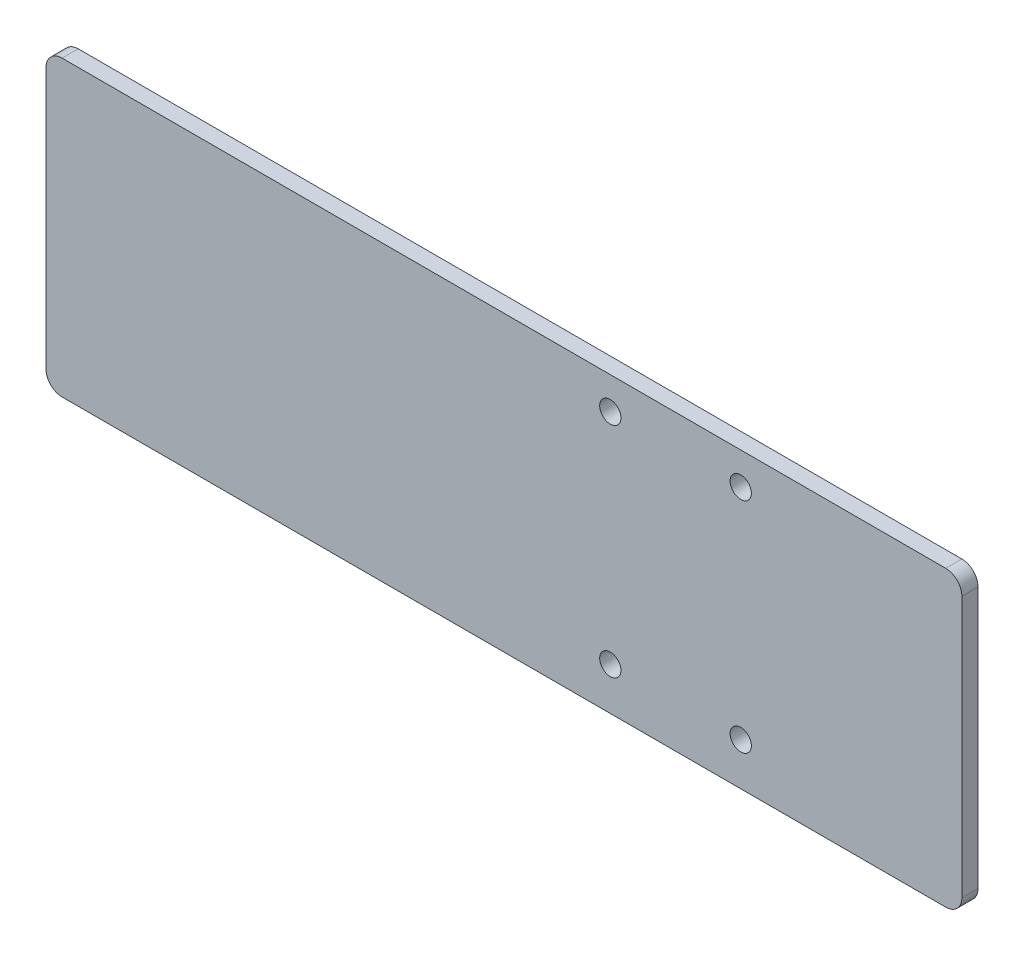
SolidWorks part; units mm, degrees
ref_plane "Front Plane" through (0, 0, 0) normal (0, 0, 1) x (1, 0, 0)
ref_plane "Top Plane" through (0, 0, 0) normal (0, 1, 0) x (1, 0, 0)
ref_plane "Right Plane" through (0, 0, 0) normal (1, 0, 0) x (0, 0, -1)
sketch "Sketch1" plane through (0, 0, 0) normal (0, 0, 1) x (1, 0, 0)
  line L1 (-137, -45.5) -> (137, -45.5)
  line L2 (-142, -40.5) -> (-142, 40.5)
  line L3 (-137, 45.5) -> (137, 45.5)
  line L4 (142, -40.5) -> (142, 40.5)
  line L5 (-142, -45.5) -> (142, 45.5) construction
  line L6 (-142, 45.5) -> (142, -45.5) construction
  arc A0 (142, 40.5) -> (137, 45.5) centre (137, 40.5) ccw
  arc A1 (142, -40.5) -> (137, -45.5) centre (137, -40.5) cw
  arc A2 (-137, -45.5) -> (-142, -40.5) centre (-137, -40.5) cw
  arc A3 (-142, 40.5) -> (-137, 45.5) centre (-137, 40.5) cw
  point P0 (0, 0)
  dimension "D3" = 5
  dimension "D1" = 91
  dimension "D2" = 284
extrude "Boss-Extrude1" add sketch "Sketch1" along normal blind 5
hole_wizard "M6 Clearance Hole2" positions "Sketch5" profile "Sketch4" hole size "M6" standard "ANSI Metric"
sketch "Sketch5" plane through (0, 0, 0) normal (0, 0, -1) x (-1, 0, 0)
  point P0 (-73.4316, -32.2992)
  point P2 (-32.9877, -32.2992)
  point P4 (-32.9877, 35.5092)
  point P6 (-73.4316, 35.5092)
sketch "Sketch4" plane through (73.4316, -32.2992, 0) normal (1, 0, 0) x (0, 1, 0)
  line L0 (0, 0) -> (0, 7.9828)
  line L1 (0, 7.9828) -> (3.3, 6)
  line L2 (3.3, 6) -> (3.3, 0)
  line L5 (3.3, 0) -> (0, 0)
  line L10 (0, 7.9828) -> (-3.3, 6) construction
  line L11 (0, -6.35) -> (0, 107.95) construction
  dimension "Hole Dia." = 6.6
  dimension "Hole Depth" = 6
  dimension "Drill Angle" = 118
sketch "Sketch7" plane through (0, 0, 0) normal (0, 0, -1) x (-1, 0, 0)
  line L8 (-142, 40.5) -> (-142, -40.5)
  line L9 (-137, -45.5) -> (137, -45.5)
  line L10 (142, -40.5) -> (142, 40.5)
  line L11 (137, 45.5) -> (-137, 45.5)
  line L12 (-142, 40.5) -> (-142, -40.5)
  line L13 (-137, -45.5) -> (137, -45.5)
  line L14 (142, -40.5) -> (142, 40.5)
  line L15 (137, 45.5) -> (-137, 45.5)
  arc A8 (-137, 45.5) -> (-142, 40.5) centre (-137, 40.5) ccw
  arc A9 (-142, -40.5) -> (-137, -45.5) centre (-137, -40.5) ccw
  arc A10 (137, -45.5) -> (142, -40.5) centre (137, -40.5) ccw
  arc A11 (142, 40.5) -> (137, 45.5) centre (137, 40.5) ccw
  arc A12 (-137, 45.5) -> (-142, 40.5) centre (-137, 40.5) ccw
  arc A13 (-142, -40.5) -> (-137, -45.5) centre (-137, -40.5) ccw
  arc A14 (137, -45.5) -> (142, -40.5) centre (137, -40.5) ccw
  arc A15 (142, 40.5) -> (137, 45.5) centre (137, 40.5) ccw
  dimension "D1" = 0
extrude "Boss-Extrude2" [suppressed] add sketch "Sketch7" along normal blind 162
